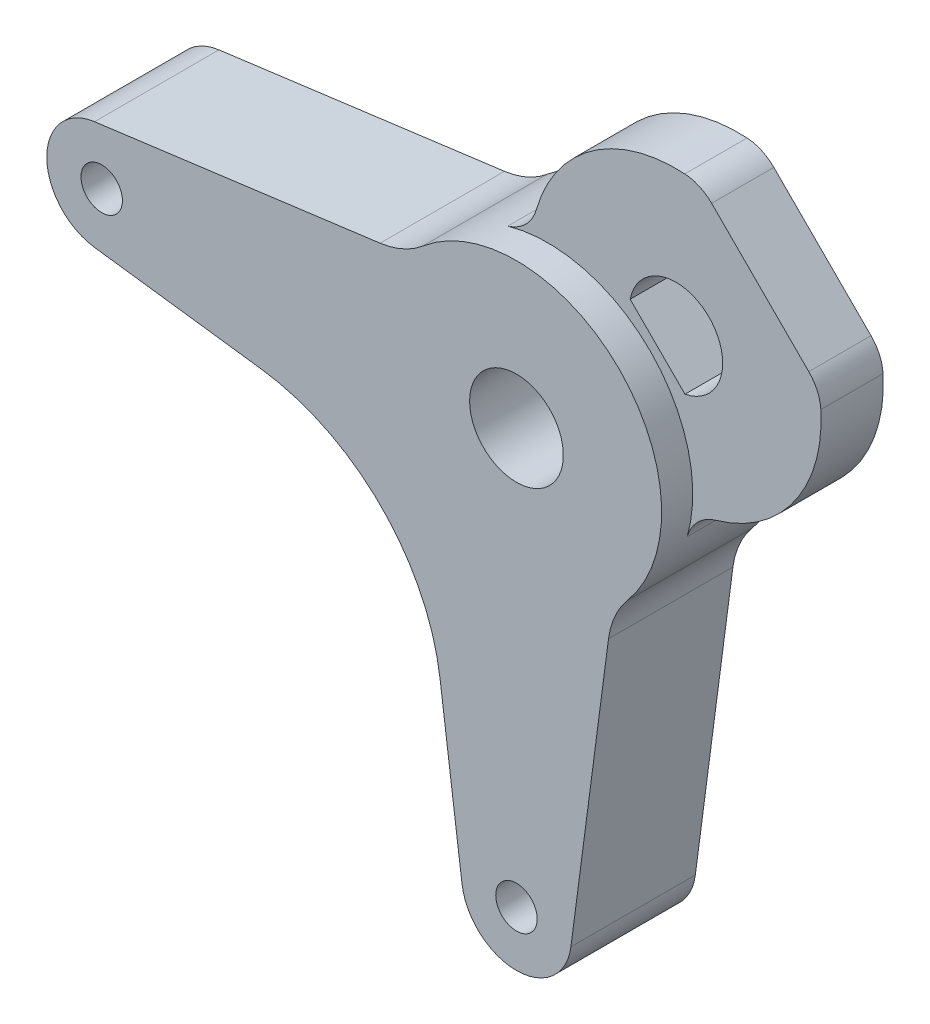
SolidWorks part; units mm, degrees
ref_plane "Front Plane" through (0, 0, 0) normal (0, 0, 1) x (1, 0, 0)
ref_plane "Top Plane" through (0, 0, 0) normal (0, 1, 0) x (1, 0, 0)
ref_plane "Right Plane" through (0, 0, 0) normal (1, 0, 0) x (0, 0, -1)
sketch "Sketch1" plane through (0, 0, 0) normal (0, 0, 1) x (1, 0, 0)
  line L0 (0, 0) -> (0, -117.8421) construction
  line L1 (0, 0) -> (-141.3474, 0) construction
  line L2 (-129.1948, -16.6709) -> (-78.07, -23.4017)
  line L3 (-16.6709, -129.1948) -> (-23.4017, -78.07)
  line L4 (-129.1948, 16.6709) -> (-41.7527, 28.1829)
  line L5 (16.6709, -129.1948) -> (28.1829, -41.7527)
  circle A0 centre (0, 0) radius 14.351
  circle A1 centre (-127, 0) radius 6.35
  circle A2 centre (0, -127) radius 6.35
  arc A3 (-129.1948, 16.6709) -> (-129.1948, -16.6709) centre (-127, 0) ccw
  arc A4 (-16.6709, -129.1948) -> (16.6709, -129.1948) centre (0, -127) ccw
  arc A5 (33.9599, -28.6797) -> (-28.6797, 33.9599) centre (0, 0) ccw
  arc A6 (-23.4017, -78.07) -> (-78.07, -23.4017) centre (-86.3584, -86.3584) ccw
  arc A7 (-41.7527, 28.1829) -> (-28.6797, 33.9599) centre (-45.0681, 53.3656) ccw
  arc A8 (33.9599, -28.6797) -> (28.1829, -41.7527) centre (53.3656, -45.0681) ccw
  dimension "D1" = 28.702
  dimension "D2" = 12.7
  dimension "D5" = 33.6296
  dimension "D6" = 88.9
  dimension "D11" = 127
  dimension "D12" = 50.8
  dimension "D13" = 50.8
  dimension "D3" = 127
  dimension "D4" = 127
  dimension "D7" = 7.5
  dimension "D8" = 7.5
  dimension "D9" = 7.5
  dimension "D10" = 7.5
extrude "Boss-Extrude2" add sketch "Sketch1" along normal mid plane 38.1 contours A8 A5 A7 L4 A3 L2 A6 L3 A4 L5 A2 A1 A0
sketch "Sketch3" plane through (0, 0, 0) normal (0, 0, 1) x (1, 0, 0)
  line L0 (0, 0) -> (0, -127) construction
  line L1 (0, 0) -> (159.9869, 159.9869) construction
  line L2 (25.2812, 42.0707) -> (42.0707, 25.2812)
  line L3 (47.1463, 83.0674) -> (83.0674, 47.1463)
  line L4 (0, 0) -> (74.5764, -74.5764) construction
  arc A0 (47.1463, 83.0674) -> (-4.8694, 44.1825) centre (39.313, 39.313) ccw
  arc A1 (42.0707, 25.2812) -> (25.2812, 42.0707) centre (39.313, 39.313) ccw
  arc A2 (33.9599, -28.6797) -> (-28.6797, 33.9599) centre (0, 0) ccw construction
  arc A3 (44.1825, -4.8694) -> (-4.8694, 44.1825) centre (0, 0) ccw
  arc A4 (44.1825, -4.8694) -> (83.0674, 47.1463) centre (39.313, 39.313) ccw
  dimension "D2" = 88.9
  dimension "D3" = 28.6004
  dimension "D1" = 135
  dimension "D4" = 47.625
  dimension "D5" = 92.075
  dimension "D6" = 50.8
extrude "Boss-Extrude3" add sketch "Sketch3" along normal mid plane 19.05
fillet "Fillet1" radius 12.7 4 edges at (44.1825, -4.8694, 0) (83.0674, 47.1463, 0) (47.1463, 83.0674, 0) (-4.8694, 44.1825, 0)
